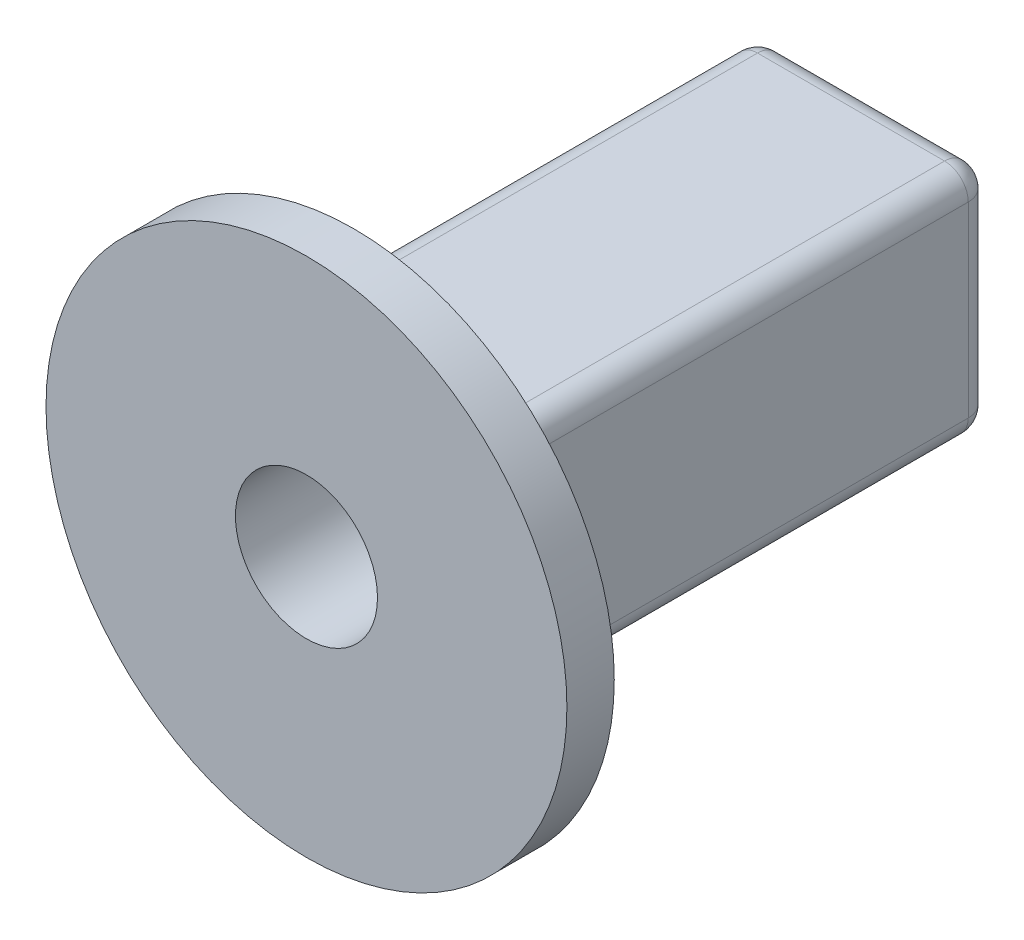
SolidWorks part; units mm, degrees
material "ABS"
ref_plane "Plan de face" through (0, 0, 0) normal (0, 0, 1) x (1, 0, 0)
ref_plane "Plan de dessus" through (0, 0, 0) normal (0, 1, 0) x (1, 0, 0)
ref_plane "Plan de droite" through (0, 0, 0) normal (1, 0, 0) x (0, 0, -1)
sketch "Esquisse1" plane through (0, 0, 0) normal (0, 0, 1) x (1, 0, 0)
  line L0 (-2.4749, 2.4749) -> (2.4749, -2.4749) construction
  line L1 (-2.4749, 2.4749) -> (2.4749, 2.4749)
  line L2 (-2.4749, 2.4749) -> (-2.4749, -2.4749)
  line L3 (-2.4749, -2.4749) -> (2.4749, -2.4749)
  line L4 (2.4749, 2.4749) -> (2.4749, -2.4749)
  line L5 (2.4749, 2.4749) -> (-2.4749, -2.4749) construction
  circle A0 centre (0, 0) radius 3.5 construction
  point P7 (0, 0)
  dimension "D1" = 7
extrude "Extrusion1" add sketch "Esquisse1" along normal blind 11
sketch "Esquisse2" plane through (0, 0, 11) normal (0, 0, 1) x (1, 0, 0)
  circle A0 centre (0, 0) radius 5.5
  dimension "D1" = 11
extrude "Extrusion2" add sketch "Esquisse2" along normal blind 1
sketch "Esquisse3" plane through (0, 0, 12) normal (0, 0, 1) x (1, 0, 0)
  circle A0 centre (0, 0) radius 1.5
  dimension "D1" = 3
extrude "Extrusion3" cut sketch "Esquisse3" against normal through all
fillet "Congé1" radius 0.5 8 edges at (2.4749, 2.4749, 5.5) (2.4749, 0, 0) (0, 2.4749, 0) (-2.4749, -2.4749, 5.5) (0, -2.4749, 0) (-2.4749, 0, 0) (2.4749, -2.4749, 5.5) (-2.4749, 2.4749, 5.5)
